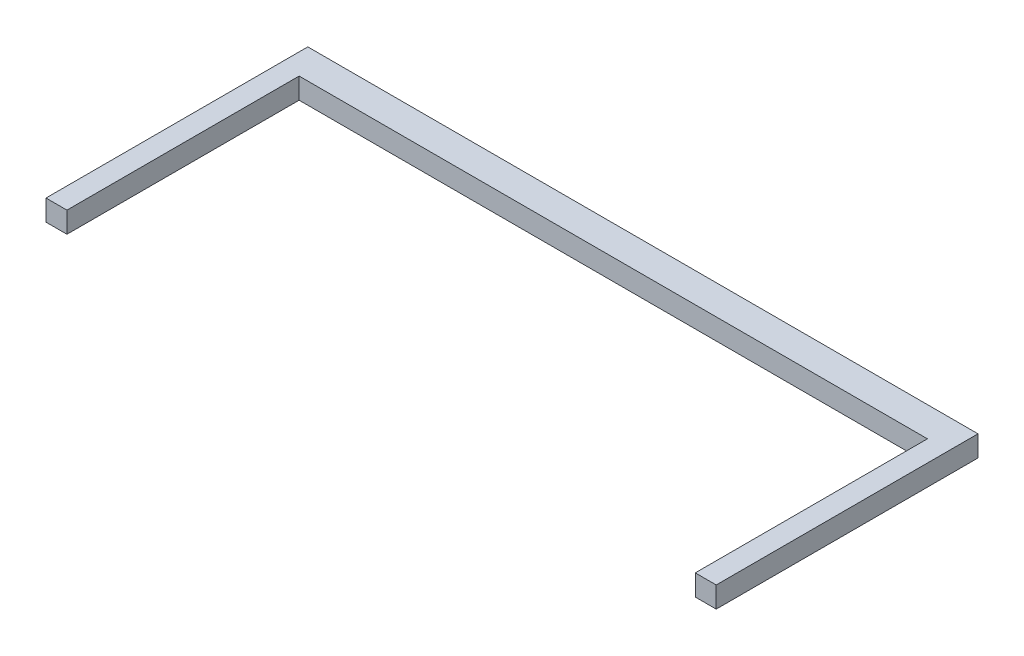
SolidWorks part; units mm, degrees
ref_plane "Front Plane" through (0, 0, 0) normal (0, 0, 1) x (1, 0, 0)
ref_plane "Top Plane" through (0, 0, 0) normal (0, 1, 0) x (1, 0, 0)
ref_plane "Right Plane" through (0, 0, 0) normal (1, 0, 0) x (0, 0, -1)
sketch "Sketch1" plane through (0, 0, 0) normal (0, 1, 0) x (1, 0, 0)
  line L0 (0, 0) -> (0, -250)
  line L1 (0, -250) -> (20, -250)
  line L2 (640, -250) -> (640, 0)
  line L3 (20, -28.2843) -> (20, -230)
  line L5 (620, -230) -> (620, -28.2843)
  line L6 (0, 0) -> (20, 0)
  line L7 (620, 0) -> (640, 0)
  line L8 (20, -28.2843) -> (620, -28.2843)
  line L9 (20, 0) -> (620, 0)
  line L10 (20, -230) -> (20, -250)
  line L11 (620, -230) -> (620, -250)
  line L12 (620, -250) -> (640, -250)
  line L13 (20, -230) -> (620, -230) construction
  line L14 (0, -250) -> (640, -250) construction
  line L15 (620, -230) -> (620, 0) construction
  line L16 (20, 0) -> (20, -230) construction
  dimension "D1" = 250
  dimension "D2" = 640
  dimension "D3" = 20
extrude "Boss-Extrude1" add sketch "Sketch1" along normal blind 20
